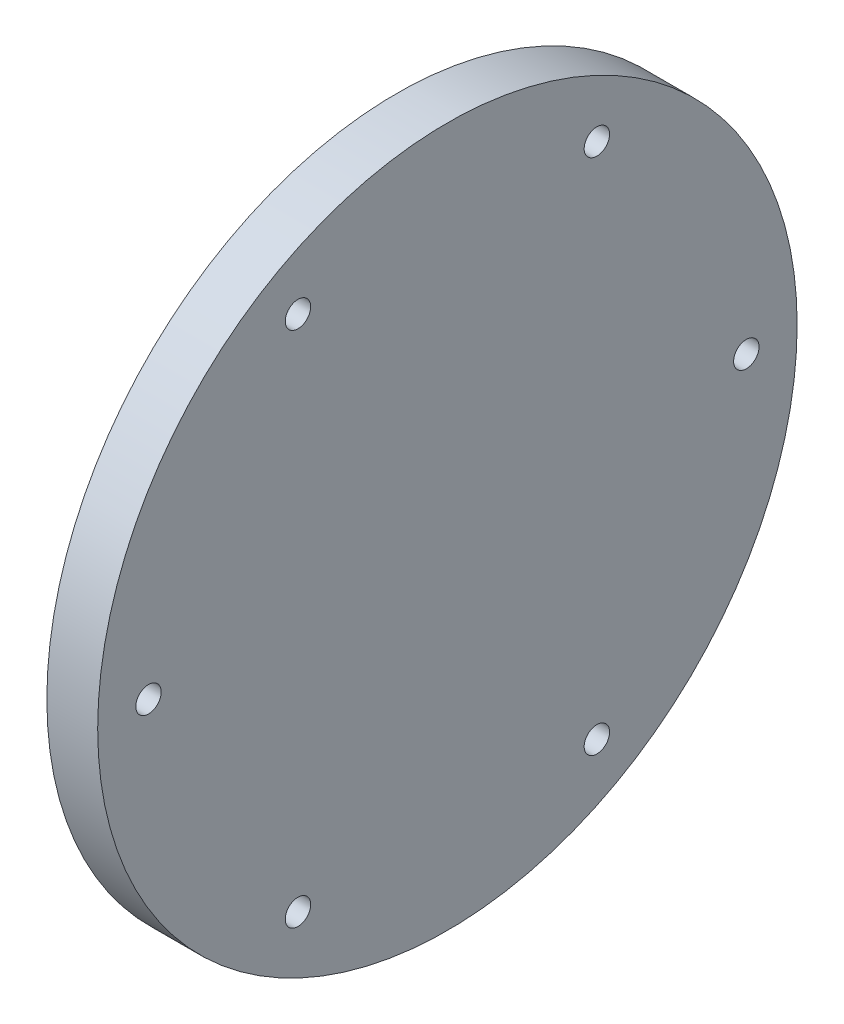
SolidWorks part; units mm, degrees
material "Copper"
ref_plane "Front Plane" through (0, 0, 0) normal (0, 0, 1) x (1, 0, 0)
ref_plane "Top Plane" through (0, 0, 0) normal (0, 1, 0) x (1, 0, 0)
ref_plane "Right Plane" through (0, 0, 0) normal (1, 0, 0) x (0, 0, -1)
sketch "Axial profile (mm)" plane through (0, 0, 0) normal (0, 0, 1) x (1, 0, 0)
  line L0 (-110, 0) -> (75, 0) construction
  line L1 (163.7, 0) -> (168.7, 0)
  line L2 (168.7, 0) -> (168.7, 34.4)
  line L3 (168.7, 34.4) -> (163.7, 34.4)
  line L4 (163.7, 34.4) -> (163.7, 0)
revolve "Full revolution" add sketch "Axial profile (mm)" angle 360 about L0
sketch "Sketch2" plane through (0, 0, 0) normal (1, 0, 0) x (0, 0, -1)
  circle A0 centre (-29.4, 0) radius 1.25
  circle A1 centre (14.7, -25.4611) radius 1.25
  circle A2 centre (14.7, 25.4611) radius 1.25
  circle A3 centre (29.4, 0) radius 1.25
  circle A4 centre (-14.7, 25.4611) radius 1.25
  circle A5 centre (-14.7, -25.4611) radius 1.25
extrude "Axial holes" cut sketch "Sketch2" along normal through all and the other way through all
